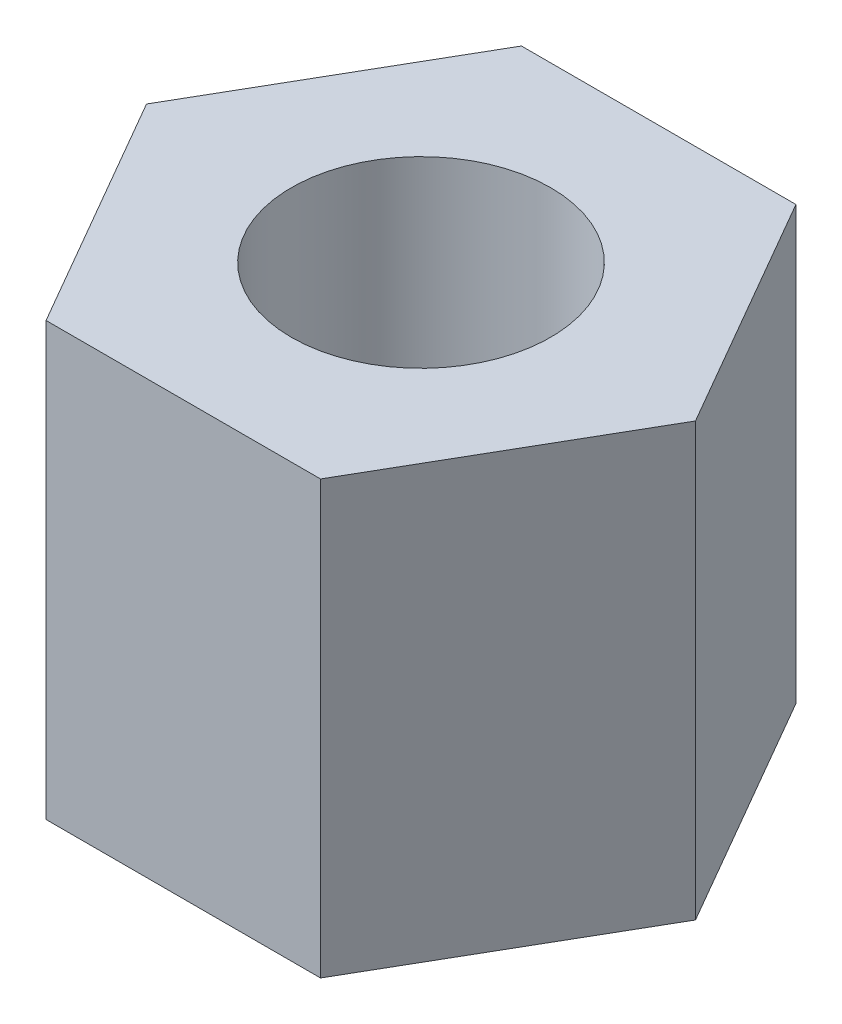
SolidWorks part; units mm, degrees
ref_plane "Plan de face" through (0, 0, 0) normal (0, 0, 1) x (1, 0, 0)
ref_plane "Plan de dessus" through (0, 0, 0) normal (0, 1, 0) x (1, 0, 0)
ref_plane "Plan de droite" through (0, 0, 0) normal (1, 0, 0) x (0, 0, -1)
sketch "Esquisse1" plane through (0, 0, 0) normal (0, 1, 0) x (1, 0, 0)
  line L0 (-3.1754, 0) -> (3.1754, 0) construction
  line L1 (1.5877, 2.75) -> (-1.5877, 2.75)
  line L2 (-1.5877, 2.75) -> (-3.1754, 0)
  line L3 (-3.1754, 0) -> (-1.5877, -2.75)
  line L4 (-1.5877, -2.75) -> (1.5877, -2.75)
  line L5 (1.5877, -2.75) -> (3.1754, 0)
  line L6 (3.1754, 0) -> (1.5877, 2.75)
  circle A0 centre (0, 0) radius 2.75 construction
  circle A1 centre (0, 0) radius 1.5
  dimension "D2" = 3
  dimension "D1" = 5.5
extrude "Boss.-Extru.1" add sketch "Esquisse1" along normal blind 5
